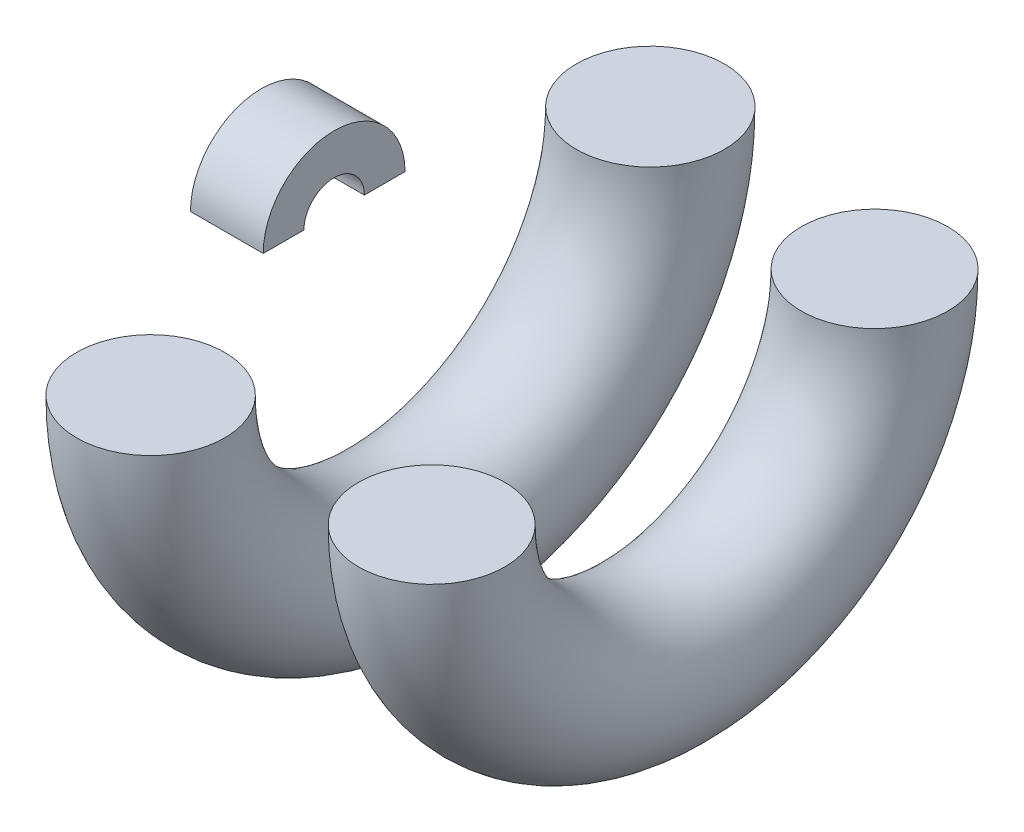
SolidWorks part; units mm, degrees
ref_plane "Front Plane" through (0, 0, 0) normal (0, 0, 1) x (1, 0, 0)
ref_plane "Top Plane" through (0, 0, 0) normal (0, 1, 0) x (1, 0, 0)
ref_plane "Right Plane" through (0, 0, 0) normal (1, 0, 0) x (0, 0, -1)
sketch "Sketch1" plane through (0, 0, 0) normal (0, 0, 1) x (1, 0, 0)
  line L0 (0, 0) -> (0, 71.1493) construction
  line L1 (59.656, -9.0305) -> (165.8326, -9.0305)
  line L2 (59.656, -9.0305) -> (59.656, 50.3518)
  line L3 (59.656, 50.3518) -> (165.8326, 50.3518)
  line L4 (165.8326, -9.0305) -> (165.8326, 50.3518)
  line L5 (0, -53.0883) -> (158.9913, -53.0883) construction
  line L6 (182.1492, -150.9399) -> (300.1774, -32.9117) construction
  line L7 (138.4561, 159.4515) -> (300.1774, 89.656) construction
  circle A0 centre (631.1987, -376.1484) radius 106.7991
  circle A1 centre (262.6451, -417.5676) radius 108.0623
  point P17 (631.1987, -376.1484)
revolve "Revolve1" add sketch "Sketch1" angle 180 mid plane about L5
